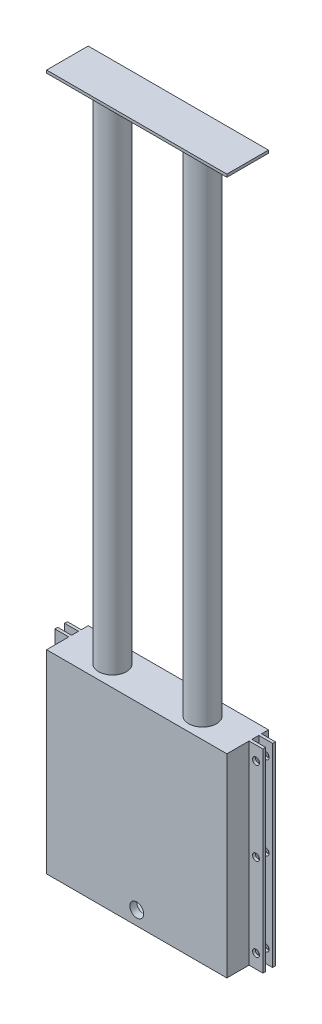
SolidWorks part; units mm, degrees
ref_plane "Front Plane" through (0, 0, 0) normal (0, 0, 1) x (1, 0, 0)
ref_plane "Top Plane" through (0, 0, 0) normal (0, 1, 0) x (1, 0, 0)
ref_plane "Right Plane" through (0, 0, 0) normal (1, 0, 0) x (0, 0, -1)
sketch "Sketch1" plane through (0, 0, 0) normal (0, 1, 0) x (1, 0, 0)
  line L0 (-82.55, 0) -> (82.55, 0) construction
  line L1 (76.2, 0) -> (82.55, 0)
  line L2 (-82.55, 0) -> (-76.2, 0)
  line L3 (-82.55, 0) -> (-82.55, 38.1)
  line L4 (-82.55, 38.1) -> (82.55, 38.1)
  line L5 (82.55, 0) -> (82.55, 38.1)
  line L7 (-76.2, 0) -> (-76.2, 31.75)
  line L8 (-76.2, 31.75) -> (76.2, 31.75)
  line L9 (76.2, 0) -> (76.2, 31.75)
  point P3 (0, 0)
  dimension "D1" = 165.1
  dimension "D2" = 38.1
  dimension "D3" = 6.35
  dimension "D4" = 6.35
  dimension "D5" = 6.35
extrude "Boss-Extrude1" add sketch "Sketch1" along normal blind 177.8 contours L4 L5 L1 L9 L8 L7 L2 L3
sketch "Sketch2" plane through (0, 177.8, 0) normal (0, 1, 0) x (1, 0, 0)
  line L0 (82.55, 0) -> (82.55, 38.1) construction
  line L1 (82.55, 31.75) -> (95.25, 31.75)
  line L2 (82.55, 31.75) -> (82.55, 29.21)
  line L3 (82.55, 29.21) -> (95.25, 29.21)
  line L4 (95.25, 31.75) -> (95.25, 29.21)
  line L5 (-82.55, 38.1) -> (82.55, 38.1) construction
  line L6 (82.55, 22.86) -> (95.25, 22.86)
  line L7 (82.55, 22.86) -> (82.55, 20.32)
  line L8 (82.55, 20.32) -> (95.25, 20.32)
  line L9 (95.25, 22.86) -> (95.25, 20.32)
  line L10 (0, 0) -> (0, 38.1) construction
  line L11 (-95.25, 22.86) -> (-95.25, 20.32)
  line L12 (-82.55, 20.32) -> (-95.25, 20.32)
  line L13 (-82.55, 22.86) -> (-82.55, 20.32)
  line L14 (-82.55, 22.86) -> (-95.25, 22.86)
  line L15 (-95.25, 31.75) -> (-95.25, 29.21)
  line L16 (-82.55, 29.21) -> (-95.25, 29.21)
  line L17 (-82.55, 31.75) -> (-82.55, 29.21)
  line L18 (-82.55, 31.75) -> (-95.25, 31.75)
  dimension "D1" = 6.35
  dimension "D2" = 2.54
  dimension "D3" = 12.7
  dimension "D4" = 6.35
extrude "Boss-Extrude2" add sketch "Sketch2" against normal up to surface (177.8 mm away) up to face at (0, 0, -17.4625)
sketch "Sketch3" plane through (0, 0, -20.32) normal (0, 0, 1) x (1, 0, 0)
  line L0 (88.9, 0) -> (88.9, 177.8) construction
  line L1 (82.55, 0) -> (95.25, 0) construction
  line L2 (82.55, 177.8) -> (95.25, 177.8) construction
  line L3 (0, 0) -> (0, 177.8) construction
  line L4 (-76.2, 177.8) -> (76.2, 177.8) construction
  circle A0 centre (88.9, 12.7) radius 3.175
  circle A1 centre (88.9, 88.9) radius 3.175
  circle A2 centre (88.9, 165.1) radius 3.175
  circle A3 centre (-88.9, 12.7) radius 3.175
  circle A4 centre (-88.9, 165.1) radius 3.175
  circle A5 centre (-88.9, 88.9) radius 3.175
  dimension "D1" = 6.35
  dimension "D2" = 12.7
  dimension "D4" = 76.2
  dimension "D3" = 3
extrude "Cut-Extrude1" cut sketch "Sketch3" against normal through all
sketch "Sketch4" plane through (-76.2, 0, 0) normal (1, 0, 0) x (0, 0, -1)
  line L0 (31.75, 0) -> (31.75, 177.8) construction
  line L1 (0, 0) -> (31.75, 0)
  line L2 (0, 0) -> (0, 6.35)
  line L3 (0, 6.35) -> (31.75, 6.35)
  line L4 (31.75, 0) -> (31.75, 6.35)
  dimension "D1" = 6.35
extrude "Boss-Extrude3" add sketch "Sketch4" along normal up to surface (152.4 mm away) up to face at (76.2, 88.9, -15.875)
fillet "Fillet1" radius 2.54 3 edges at (76.2, 6.35, -15.875) (-76.2, 6.35, -15.875) (0, 6.35, -31.75)
sketch "Sketch5" plane through (-76.2, 0, 0) normal (1, 0, 0) x (0, 0, -1)
  line L0 (31.75, 177.8) -> (31.75, 8.89) construction
  line L1 (0, 177.8) -> (31.75, 177.8)
  line L2 (0, 177.8) -> (0, 171.45)
  line L3 (0, 171.45) -> (31.75, 171.45)
  line L4 (31.75, 177.8) -> (31.75, 171.45)
  dimension "D1" = 6.35
extrude "Boss-Extrude4" add sketch "Sketch5" along normal up to next
sketch "Sketch6" plane through (0, 0, 0) normal (0, 0, 1) x (1, 0, 0)
  line L0 (76.2, 171.45) -> (-76.2, 171.45) construction
  line L1 (-76.2, 171.45) -> (-76.2, 8.89) construction
  line L3 (73.66, 6.35) -> (-73.66, 6.35) construction
  line L4 (76.2, 171.45) -> (76.2, 8.89) construction
  line L5 (76.2, 171.45) -> (76.2, 8.89)
  line L6 (73.66, 6.35) -> (-73.66, 6.35)
  line L7 (-76.2, 171.45) -> (-76.2, 8.89)
  line L8 (76.2, 171.45) -> (-76.2, 171.45)
  arc A0 (-76.2, 8.89) -> (-73.66, 6.35) centre (-73.66, 8.89) ccw construction
  arc A1 (73.66, 6.35) -> (76.2, 8.89) centre (73.66, 8.89) ccw construction
  arc A2 (-76.2, 8.89) -> (-73.66, 6.35) centre (-73.66, 8.89) ccw
  arc A3 (73.66, 6.35) -> (76.2, 8.89) centre (73.66, 8.89) ccw
extrude "Boss-Extrude5" add sketch "Sketch6" against normal blind 6.35
sketch "Sketch7" plane through (0, 0, 0) normal (0, -1, 0) x (1, 0, 0)
  line L0 (0, 0) -> (0, -38.1) construction
  line L1 (-82.55, -38.1) -> (82.55, -38.1) construction
  line L2 (-12.7, 0) -> (-12.7, -6.35)
  line L3 (-12.7, 0) -> (12.7, 0)
  line L5 (-12.7, -6.35) -> (12.7, -6.35)
  line L6 (12.7, 0) -> (12.7, -6.35)
  line L7 (0, -19.05) -> (82.55, -19.05) construction
  line L8 (82.55, 0) -> (82.55, -20.32) construction
  line L9 (12.7, -38.1) -> (12.7, -31.75)
  line L10 (-12.7, -31.75) -> (12.7, -31.75)
  line L11 (-12.7, -38.1) -> (12.7, -38.1)
  line L12 (-12.7, -38.1) -> (-12.7, -31.75)
  dimension "D1" = 25.4
  dimension "D2" = 6.35
extrude "Boss-Extrude6" add sketch "Sketch7" along normal blind 12.7
sketch "Sketch8" plane through (0, -12.7, 0) normal (0, -1, 0) x (1, 0, 0)
  line L0 (0, 0) -> (0, -38.1) construction
  line L1 (12.7, 0) -> (-12.7, 0) construction
  line L2 (-12.7, -38.1) -> (12.7, -38.1) construction
  line L3 (0, 0) -> (12.7, 0)
  line L4 (12.7, 0) -> (12.7, -6.35)
  line L5 (12.7, -6.35) -> (0, -6.35)
  line L6 (-12.7, -6.35) -> (12.7, -6.35) construction
  line L7 (0, -31.75) -> (12.7, -31.75)
  line L8 (12.7, -31.75) -> (-12.7, -31.75) construction
  line L9 (12.7, -31.75) -> (12.7, -38.1)
  line L10 (12.7, -38.1) -> (0, -38.1)
  line L11 (0, 0) -> (0, -6.35)
  line L12 (0, -31.75) -> (0, -38.1)
revolve "Revolve1" add sketch "Sketch8" angle 180 about L0
sketch "Sketch10" plane through (0, 0, -38.1) normal (0, 0, -1) x (-1, 0, 0)
  line L0 (12.7, -12.7) -> (12.7, 0) construction
  line L1 (-12.7, -12.7) -> (-12.7, 0) construction
  line L2 (12.7, -12.7) -> (12.7, 0)
  line L3 (-12.7, -12.7) -> (-12.7, 0)
  line L4 (-12.7, -12.7) -> (12.7, -12.7) construction
  line L5 (0, 0) -> (0, -25.4) construction
  arc A0 (-12.7, -12.7) -> (12.7, -12.7) centre (0, -12.7) ccw construction
  circle A1 centre (0, -12.7) radius 6.35
  dimension "D1" = 12.7
extrude "Cut-Extrude2" cut sketch "Sketch10" against normal through all contours A1
sketch "Sketch11" plane through (0, 177.8, 0) normal (0, 1, 0) x (1, 0, 0)
  line L0 (0, 0) -> (0, 38.1) construction
  line L1 (-82.55, 38.1) -> (82.55, 38.1) construction
  line L2 (0, 19.05) -> (-82.55, 19.05) construction
  line L3 (-82.55, 0) -> (-82.55, 20.32) construction
  line L4 (-41.275, 19.05) -> (-41.275, 38.1) construction
  circle A0 centre (-41.275, 19.05) radius 12.7
  circle A1 centre (41.275, 19.05) radius 12.7
  dimension "D1" = 25.4
extrude "Boss-Extrude7" add sketch "Sketch11" along normal blind 457.2
sketch "Sketch12" plane through (0, 635, 0) normal (0, 1, 0) x (1, 0, 0)
  line L0 (82.55, 0) -> (82.55, 20.32) construction
  line L1 (82.55, 22.86) -> (82.55, 29.21) construction
  line L2 (82.55, 31.75) -> (82.55, 38.1) construction
  line L3 (-82.55, 31.75) -> (-82.55, 38.1) construction
  line L4 (-82.55, 22.86) -> (-82.55, 29.21) construction
  line L5 (-82.55, 0) -> (-82.55, 20.32) construction
  line L6 (-82.55, 0) -> (82.55, 0) construction
  line L7 (-82.55, 38.1) -> (82.55, 38.1) construction
  line L8 (82.55, 0) -> (82.55, 20.32)
  line L9 (82.55, 22.86) -> (82.55, 29.21)
  line L10 (82.55, 31.75) -> (82.55, 38.1)
  line L11 (-82.55, 31.75) -> (-82.55, 38.1)
  line L12 (-82.55, 22.86) -> (-82.55, 29.21)
  line L13 (-82.55, 0) -> (-82.55, 20.32)
  line L14 (-82.55, 0) -> (82.55, 0)
  line L15 (-82.55, 38.1) -> (82.55, 38.1)
  line L16 (-82.55, 31.75) -> (-82.55, 29.21)
  line L17 (-82.55, 22.86) -> (-82.55, 20.32)
  line L18 (82.55, 31.75) -> (82.55, 29.21)
  line L19 (82.55, 22.86) -> (82.55, 20.32)
extrude "Boss-Extrude8" add sketch "Sketch12" along normal blind 2.54
mirror "Mirror1" about plane through (0, 0, 0) normal (0, 1, 0) of "Cut-Extrude2"
sketch "Sketch13" plane through (0, 0, 0) normal (0, 0, 1) x (1, 0, 0)
  line L0 (-12.7, 0) -> (12.7, 0)
  line L1 (12.7, -12.7) -> (12.7, 0) construction
  line L2 (-12.7, -12.7) -> (-12.7, 0) construction
  line L3 (12.7, -12.7) -> (12.7, 0)
  line L4 (-12.7, -12.7) -> (-12.7, 0)
  arc A0 (-12.7, -12.7) -> (12.7, -12.7) centre (0, -12.7) ccw construction
  arc A1 (-12.7, -12.7) -> (12.7, -12.7) centre (0, -12.7) ccw
extrude "Cut-Extrude3" cut sketch "Sketch13" against normal through all
